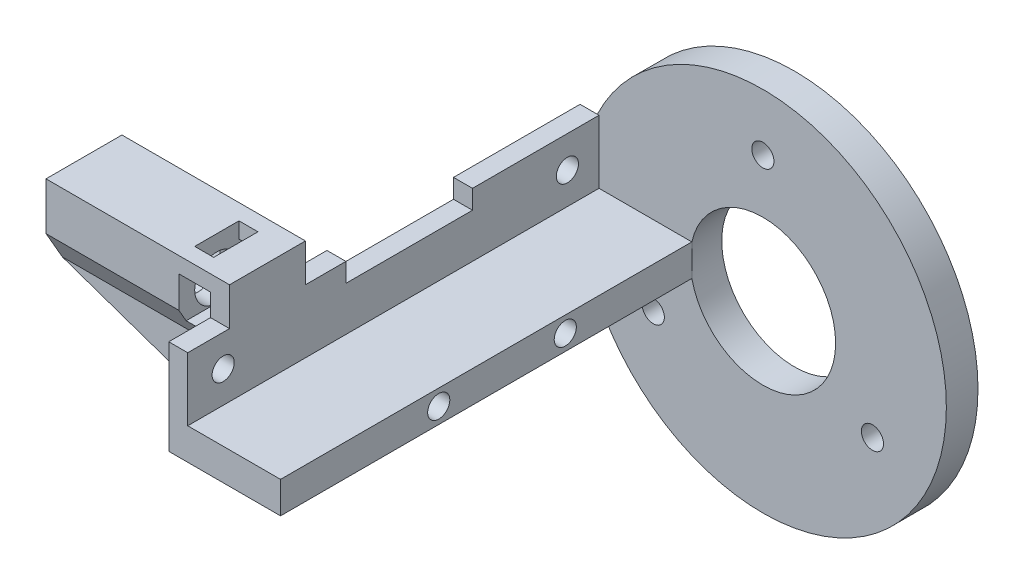
SolidWorks part; units mm, degrees
ref_plane "前视基准面" through (0, 0, 0) normal (0, 0, 1) x (1, 0, 0)
ref_plane "上视基准面" through (0, 0, 0) normal (0, 1, 0) x (1, 0, 0)
ref_plane "右视基准面" through (0, 0, 0) normal (1, 0, 0) x (0, 0, -1)
sketch "草图1" plane through (0, 0, 0) normal (0, 0, 1) x (1, 0, 0)
  circle A0 centre (0, 0) radius 29
  dimension "D1" = 58
extrude "凸台-拉伸1" add sketch "草图1" along normal blind 5
sketch "草图2" plane through (0, 0, 5) normal (0, 0, 1) x (1, 0, 0)
  line L0 (0, 0) -> (0, 20)
  line L1 (0, 0) -> (-17.3205, -10)
  line L2 (0, 0) -> (17.3205, -10)
  circle A0 centre (0, 0) radius 20
  dimension "D1" = 40
  dimension "D2" = 120
  dimension "D3" = 120
sketch "草图3" plane through (0, 0, 5) normal (0, 0, 1) x (1, 0, 0)
  point P0 (0, 20)
  point P3 (-17.3205, -10)
  point P6 (17.3205, -10)
hole_wizard "孔1" positions "草图3" profile "草图4" legacy end condition up to next
sketch "草图4" plane through (0, 20, 5) normal (1, 0, 0) x (0, -1, 0)
  line L0 (0, 0) -> (0, 5)
  line L1 (0, 5) -> (1.75, 5)
  line L2 (1.75, 5) -> (1.75, 0)
  line L3 (1.75, 0) -> (0, 0)
  line L4 (0, 110) -> (0, -10) construction
  dimension "直径" = 3.5
  dimension "深度" = 5
hole_wizard "孔2" positions "草图5" profile "草图6" legacy end condition up to next
sketch "草图5" plane through (0, 0, 5) normal (0, 0, 1) x (1, 0, 0)
  point P0 (0, 0)
sketch "草图6" plane through (0, 0, 5) normal (1, 0, 0) x (0, -1, 0)
  line L0 (0, 0) -> (0, 5)
  line L1 (0, 5) -> (11.5, 5)
  line L2 (11.5, 5) -> (11.5, 0)
  line L3 (11.5, 0) -> (0, 0)
  line L4 (0, 110) -> (0, -10) construction
  dimension "直径" = 23
  dimension "深度" = 5
sketch "草图7" plane through (0, 0, 5) normal (0, 0, 1) x (1, 0, 0)
  line L1 (-28.892, -2.5) -> (28.892, -2.5)
  line L2 (-28.892, -2.5) -> (-28.892, 2.5)
  line L3 (-28.892, 2.5) -> (28.892, 2.5)
  line L4 (28.892, -2.5) -> (28.892, 2.5)
  line L5 (-28.892, -2.5) -> (28.892, 2.5) construction
  line L6 (-28.892, 2.5) -> (28.892, -2.5) construction
  circle A0 centre (0, 0) radius 29 construction
  circle A1 centre (0, 0) radius 11.4884
  circle A2 centre (0, 0) radius 29
  point P0 (0, 0)
  circle M5 centre (0, 0) radius 11.5
  dimension "D2" = 58
  dimension "D1" = 5
extrude "凸台-拉伸3" add sketch "草图7" along normal blind 65 contours L3 L2 L1 M5 | A2
sketch "草图9" plane through (0, 0, 5) normal (0, 0, 1) x (1, 0, 0)
  line L1 (-28.892, 2.5) -> (-29.892, 2.5)
  line L2 (-28.892, 2.5) -> (-28.892, -2.5)
  line L3 (-28.892, -2.5) -> (-29.892, -2.5)
  line L4 (-29.892, 2.5) -> (-29.892, -2.5)
  dimension "D1" = 5
  dimension "D2" = 1
extrude "切除-拉伸1" cut sketch "草图9" against normal blind 10
sketch "草图10" plane through (0, 2.5, 0) normal (0, 1, 0) x (1, 0, 0)
  line L0 (-28.892, -70) -> (-11.225, -70) construction
  line L1 (-28.892, -5) -> (-25.892, -5)
  line L2 (-28.892, -5) -> (-28.892, -70)
  line L3 (-28.892, -70) -> (-25.892, -70)
  line L4 (-25.892, -5) -> (-25.892, -70)
  dimension "D1" = 3
extrude "凸台-拉伸5" add sketch "草图10" along normal blind 10
sketch "草图11" plane through (-28.892, 0, 0) normal (-1, 0, 0) x (0, 0, 1)
  line L0 (10, 7.5) -> (64.4, 7.5) construction
  line L1 (5, 2.5) -> (10, 2.5) construction
  line L2 (5, 2.5) -> (5, 7.5) construction
  line L3 (5, 7.5) -> (10, 7.5) construction
  line L4 (10, 2.5) -> (10, 7.5) construction
  line L5 (57.4, 7.5) -> (57.4, 12.5)
  point P5 (57.4, 7.5)
  dimension "D1" = 5
  dimension "D2" = 5
  dimension "D3" = 54.4
  dimension "D4" = 7
  dimension "D5" = 5
sketch "草图14" plane through (-28.892, 0, 0) normal (-1, 0, 0) x (0, 0, 1)
  point P0 (10, 7.5)
  point P3 (64.4, 7.5)
hole_wizard "孔3" positions "草图14" profile "草图15" legacy end condition up to next
sketch "草图15" plane through (-28.892, 7.5, 10) normal (0, 1, 0) x (0, 0, 1)
  line L0 (0, 0) -> (0, 3)
  line L1 (0, 3) -> (1.75, 3)
  line L2 (1.75, 3) -> (1.75, 0)
  line L3 (1.75, 0) -> (0, 0)
  line L4 (0, 110) -> (0, -10) construction
  dimension "直径" = 3.5
  dimension "深度" = 3
sketch "草图16" plane through (-28.892, 0, 0) normal (-1, 0, 0) x (0, 0, 1)
  line L0 (5, 12.5) -> (70, 12.5) construction
  line L1 (25, 12.5) -> (45, 12.5)
  line L2 (25, 12.5) -> (25, 9.5)
  line L3 (25, 9.5) -> (45, 9.5)
  line L4 (45, 12.5) -> (45, 9.5)
  line L5 (5, -20) -> (5, 20) construction
  dimension "D1" = 20
  dimension "D2" = 20
  dimension "D3" = 3
extrude "切除-拉伸2" cut sketch "草图16" against normal up to next
sketch "草图17" plane through (-28.892, 0, 0) normal (-1, 0, 0) x (0, 0, 1)
  line L0 (5, 0) -> (25, 0) construction
  line L1 (5, 2.5) -> (70, 2.5) construction
  line L2 (5, 2.5) -> (5, -2.5)
  line L3 (5, -2.5) -> (70, -2.5)
  line L4 (70, 2.5) -> (70, -2.5)
  line L5 (25, 0) -> (45, 0) construction
  dimension "D1" = 20
  dimension "D2" = 20
sketch "草图18" plane through (-28.892, 0, 0) normal (-1, 0, 0) x (0, 0, 1)
  point P0 (25, 0)
  point P3 (45, 0)
sketch "草图20" plane through (0, 0, 70) normal (0, 0, 1) x (1, 0, 0)
  line L0 (-11.225, 2.5) -> (-11.225, -2.5)
  circle A0 centre (0, 0) radius 11.5
  arc M8 (-11.225, -2.5) -> (-11.225, 2.5) centre (0, 0) cw
extrude "凸台-拉伸6" add sketch "草图20" against normal blind 65 contours L0 M8
hole_wizard "孔4" positions "草图18" profile "草图19" legacy end condition through all
sketch "草图19" plane through (-28.892, 0, 25) normal (0, 1, 0) x (0, 0, 1)
  line L0 (0, 0) -> (0, 57.892)
  line L1 (0, 57.892) -> (1.75, 57.892)
  line L2 (1.75, 57.892) -> (1.75, 0)
  line L3 (1.75, 0) -> (0, 0)
  line L4 (0, 110) -> (0, -10) construction
  dimension "直径" = 3.5
  dimension "深度" = 57.892
sketch "草图21" plane through (-28.892, 0, 0) normal (-1, 0, 0) x (0, 0, 1)
  line L0 (63.4, 11) -> (60.8019, 6.5) construction
  line L1 (51.4, 6.5) -> (63.4, 6.5) construction
  line L2 (51.4, 6.5) -> (51.4, 18.5) construction
  line L3 (51.4, 18.5) -> (63.4, 18.5) construction
  line L4 (63.4, 6.5) -> (63.4, 18.5) construction
  line L5 (51.4, 6.5) -> (63.4, 18.5) construction
  line L6 (51.4, 18.5) -> (63.4, 6.5) construction
  circle A0 centre (57.4, 12.5) radius 5.2 construction
  point P0 (57.4, 12.5)
  dimension "D3" = 10.4
  dimension "D1" = 12
  dimension "D2" = 12
  dimension "D4" = 30
  dimension "D5" = 4.5
sketch "草图22" plane through (-28.892, 0, 0) normal (-1, 0, 0) x (0, 0, 1)
  line L0 (51.4, 6.5) -> (51.4, 18.5) construction
  line L1 (51.4, 12.5) -> (63.4, 12.5)
  line L2 (51.4, 12.5) -> (51.4, 18.5)
  line L3 (51.4, 18.5) -> (63.4, 18.5)
  line L4 (63.4, 12.5) -> (63.4, 18.5)
extrude "凸台-拉伸7" add sketch "草图22" against normal blind 3 contours L2 L1 L4 L3
sketch "草图23" plane through (-28.892, 0, 0) normal (-1, 0, 0) x (0, 0, 1)
  line L0 (60.8019, 6.5) -> (63.4, 11)
  line L1 (51.4, 18.5) -> (63.4, 18.5)
  line L2 (51.4, 18.5) -> (51.4, 6.5)
  line L3 (51.4, 6.5) -> (63.4, 6.5)
  line L4 (63.4, 18.5) -> (63.4, 6.5)
  line M16 (63.4, 12.5) -> (63.4, 18.5)
  line M17 (63.4, 18.5) -> (51.4, 18.5)
  line M18 (51.4, 18.5) -> (51.4, 12.5)
extrude "凸台-拉伸8" add sketch "草图23" along normal blind 8 contours L4 L2 L3 L0 M16 M17 M18
hole_wizard "孔5" positions "草图25" profile "草图26" legacy
sketch "草图25" plane through (-36.892, 0, 0) normal (-1, 0, 0) x (0, 0, 1)
  point P0 (57.4, 12.5)
sketch "草图26" plane through (-36.892, 12.5, 57.4) normal (0, 1, 0) x (0, 0, 1)
  line L0 (0, 0) -> (0, 3)
  line L1 (0, 3) -> (3.5, 3)
  line L2 (3.5, 3) -> (3.5, 0)
  line L3 (3.5, 0) -> (0, 0)
  line L4 (0, 110) -> (0, -10) construction
  dimension "直径" = 7
  dimension "深度" = 3
sketch "草图27" plane through (0, 0, 51.4) normal (0, 0, -1) x (-1, 0, 0)
  line L0 (36.892, 12.5) -> (28.892, 12.5)
  line L1 (36.892, 18.5) -> (36.892, 6.5) construction
  line L3 (28.892, 9) -> (33.892, 9)
  line L4 (28.892, 9) -> (28.892, 16)
  line L5 (28.892, 16) -> (33.892, 16)
  line L6 (33.892, 9) -> (33.892, 16)
  line L7 (28.892, 9) -> (33.892, 16) construction
  line L8 (28.892, 16) -> (33.892, 9) construction
  point P5 (31.392, 12.5)
  line M6 (28.892, 12.5) -> (28.892, 6.5)
  dimension "D1" = 3
  dimension "D2" = 5
  dimension "D3" = 7
extrude "切除-拉伸3" cut sketch "草图27" against normal through all contours L0 L6 L5 L4 | L3 L6 L0 M6
sketch "草图28" plane through (0, 18.5, 0) normal (0, 1, 0) x (1, 0, 0)
  line L0 (-36.892, -57.4) -> (-28.892, -57.4)
  line L1 (-36.892, -63.4) -> (-36.892, -51.4) construction
  line L3 (-33.892, -60.9) -> (-30.892, -60.9)
  line L4 (-33.892, -60.9) -> (-33.892, -53.9)
  line L5 (-33.892, -53.9) -> (-30.892, -53.9)
  line L6 (-30.892, -60.9) -> (-30.892, -53.9)
  line L7 (-33.892, -60.9) -> (-30.892, -53.9) construction
  line L8 (-33.892, -53.9) -> (-30.892, -60.9) construction
  point P5 (-32.392, -57.4)
  dimension "D1" = 3
  dimension "D2" = 3
  dimension "D3" = 7
extrude "切除-拉伸4" cut sketch "草图28" against normal up to next contours L3 L6 L0 L4 | L0 L6 L5 L4
sketch "草图29" plane through (-36.892, 0, 0) normal (-1, 0, 0) x (0, 0, 1)
  line L0 (51.4, 18.5) -> (63.4, 6.5) construction
  line L1 (51.4, 6.5) -> (63.4, 6.5)
  line L2 (51.4, 6.5) -> (51.4, 18.5)
  line L3 (51.4, 18.5) -> (63.4, 18.5)
  line L4 (63.4, 6.5) -> (63.4, 18.5)
  line L5 (51.4, 6.5) -> (63.4, 18.5) construction
  line L6 (51.4, 18.5) -> (63.4, 6.5) construction
  line L7 (60.8019, 6.5) -> (63.4, 11)
  point P0 (57.4, 12.5)
  circle M5 centre (57.4, 12.5) radius 3.5
  line M6 (63.4, 11) -> (63.4, 18.5)
  line M7 (63.4, 18.5) -> (51.4, 18.5)
  line M8 (51.4, 18.5) -> (51.4, 6.5)
  line M9 (51.4, 6.5) -> (60.8019, 6.5)
  line M10 (60.8019, 6.5) -> (63.4, 11)
extrude "凸台-拉伸9" add sketch "草图29" along normal blind 18 contours M10 M6 M7 M8 M9 M5 | M5
sketch "草图30" plane through (-54.892, 0, 0) normal (-1, 0, 0) x (0, 0, 1)
  point P0 (57.4, 12.5)
hole_wizard "孔6" positions "草图30" profile "草图31" legacy
sketch "草图31" plane through (-54.892, 12.5, 57.4) normal (0, 1, 0) x (0, 0, 1)
  line L0 (0, 0) -> (0, 18)
  line L1 (0, 18) -> (5.2, 18)
  line L2 (5.2, 18) -> (5.2, 0)
  line L3 (5.2, 0) -> (0, 0)
  line L4 (0, 110) -> (0, -10) construction
  dimension "直径" = 10.4
  dimension "深度" = 18
sketch "草图32" plane through (0, 6.5, 0) normal (0, -1, 0) x (1, 0, 0)
  line L0 (-28.892, 10) -> (-28.892, 64.4) construction
  line L1 (-54.892, 60.8019) -> (-28.892, 60.8019)
  line L2 (-54.892, 60.8019) -> (-54.892, 55.8019)
  line L3 (-54.892, 55.8019) -> (-28.892, 55.8019)
  line L4 (-28.892, 60.8019) -> (-28.892, 55.8019)
  dimension "D1" = 5
extrude "凸台-拉伸10" add sketch "草图32" along normal blind 9
sketch "草图33" plane through (0, 0, 60.8019) normal (0, 0, 1) x (1, 0, 0)
  line L0 (-54.892, 6.5) -> (-28.892, -2.5)
  line L1 (-28.892, -2.5) -> (-54.892, -2.5)
  line L2 (-54.892, -2.5) -> (-54.892, 6.5)
extrude "切除-拉伸5" cut sketch "草图33" against normal up to next contours L2 L0 L1
sketch "草图34" plane through (0, 0, 5) normal (0, 0, 1) x (1, 0, 0)
  line L0 (-23.892, -2.5) -> (-23.892, -16.4369)
  line L1 (-28.892, -2.5) -> (-11.225, -2.5) construction
  line L2 (-28.892, -2.5) -> (-23.892, -2.5)
  circle A0 centre (0, 0) radius 29
  line M10 (-11.225, -2.5) -> (-28.892, -2.5)
  arc M11 (-28.892, -2.5) -> (-26.1677, 12.5) centre (0, 0) ccw
  dimension "D1" = 58
  dimension "D2" = 5
extrude "凸台-拉伸11" add sketch "草图34" along normal up to surface (65 mm away) contours L0 M10 M11 up to face at (-22.003, 4.1667, 70)
sketch "草图35" plane through (-23.892, 0, 0) normal (1, 0, 0) x (0, 0, -1)
  line L3 (-70, -2.5) -> (-5, -14.4369)
  line L4 (-5, 20) -> (-5, -20) construction
  line L5 (-5, -14.4369) -> (-5, -16.4369)
  line L6 (-5, -16.4369) -> (-70, -16.4369)
  line L7 (-70, -16.4369) -> (-70, -2.5)
  dimension "D1" = 2
extrude "切除-拉伸6" cut sketch "草图35" against normal up to next
